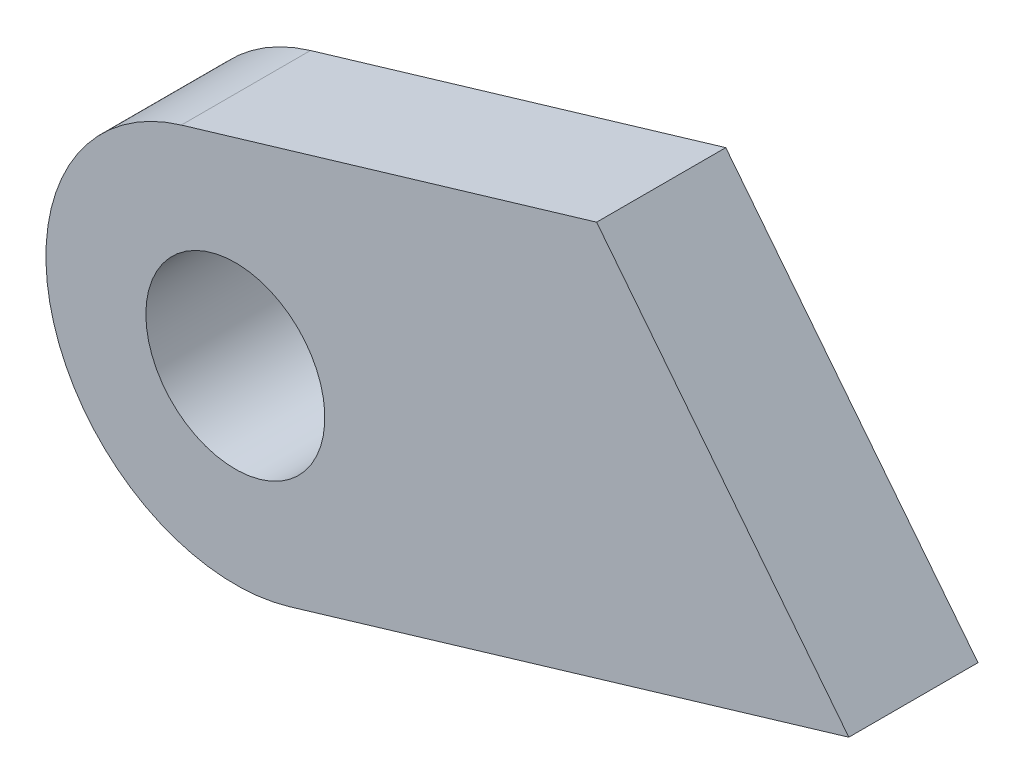
SolidWorks part; units mm, degrees
material "Alloy Steel"
ref_plane "X-Y Datum" through (0, 0, 0) normal (0, 0, 1) x (1, 0, 0)
ref_plane "X-Z Datum" through (0, 0, 0) normal (0, 1, 0) x (1, 0, 0)
ref_plane "Y-Z Datum" through (0, 0, 0) normal (1, 0, 0) x (0, 0, -1)
sketch "Sketch1" plane through (0, 0, 0) normal (0, 0, 1) x (1, 0, 0)
  line L0 (-508.2917, -95.5943) -> (-487.66, -89.4479)
  line L2 (-512.2775, -82.2049) -> (-496.9624, -77.6492)
  line L3 (-487.66, -89.4479) -> (-496.9624, -77.6492)
  circle A1 centre (-510.286, -88.9) radius 4.7 construction
  circle A2 centre (-510.286, -88.9) radius 6.985 construction
  arc A3 (-508.2917, -95.5943) -> (-512.2775, -82.2049) centre (-510.286, -88.9) cw
  circle A4 centre (-510.286, -88.9) radius 3.3
  dimension "D1" = 13.97
  dimension "D4" = 6.6
extrude "Boss-Extrude1" add sketch "Sketch1" along normal blind 4.7625
